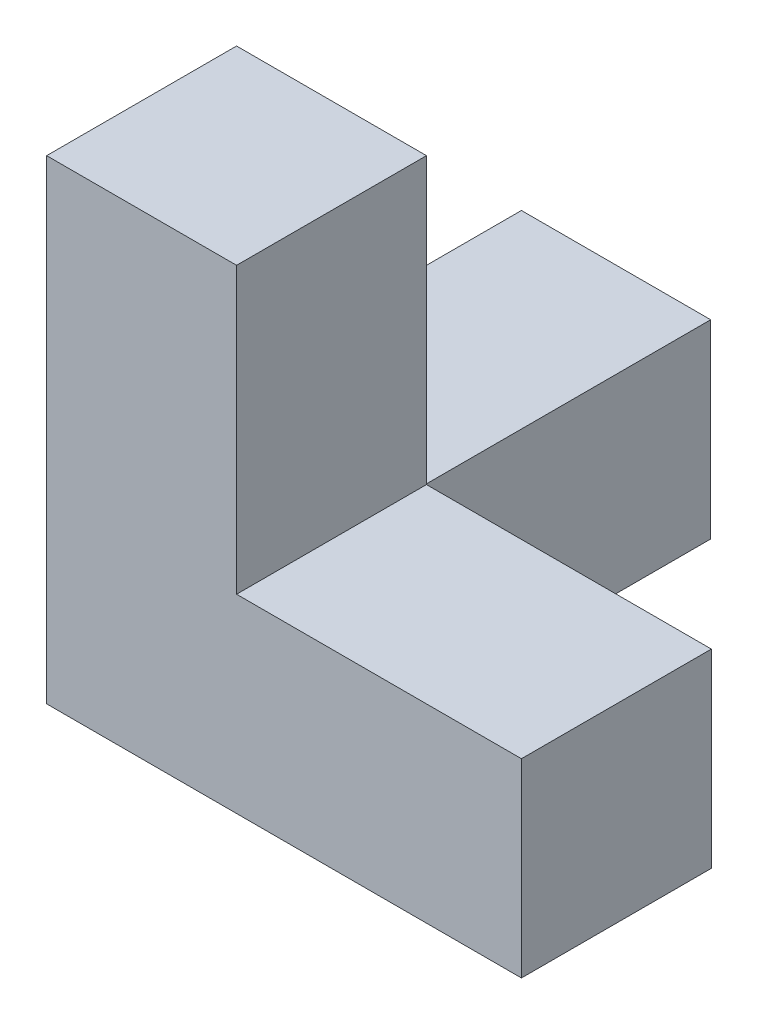
SolidWorks part; units mm, degrees
ref_plane "Plan de face" through (0, 0, 0) normal (0, 0, 1) x (1, 0, 0)
ref_plane "Plan de dessus" through (0, 0, 0) normal (0, 1, 0) x (1, 0, 0)
ref_plane "Plan de droite" through (0, 0, 0) normal (1, 0, 0) x (0, 0, -1)
sketch "Esquisse2" plane through (0, 0, 0) normal (0, 0, 1) x (1, 0, 0)
  line L1 (-109.7222, 44.9846) -> (-59.7222, 44.9846)
  line L2 (-109.7222, 44.9846) -> (-109.7222, -5.0154)
  line L3 (-109.7222, -5.0154) -> (-59.7222, -5.0154)
  line L4 (-59.7222, 44.9846) -> (-59.7222, -5.0154)
  line L5 (-109.7222, 44.9846) -> (-59.7222, -5.0154) construction
  line L6 (-109.7222, -5.0154) -> (-59.7222, 44.9846) construction
  point P0 (-84.7222, 19.9846)
  dimension "D1" = 50
  dimension "D2" = 50
  dimension "D3" = 50
  dimension "D4" = 50
extrude "Boss.-Extru.1" add sketch "Esquisse2" along normal blind 50
sketch "Esquisse3" plane through (0, 0, 50) normal (0, 0, 1) x (1, 0, 0)
  line L0 (-89.7222, 44.9846) -> (-89.7222, 14.9846)
  line L1 (-59.7222, 44.9846) -> (-109.7222, 44.9846) construction
  line L2 (-89.7222, 14.9846) -> (-59.7222, 14.9846)
  line L3 (-59.7222, -5.0154) -> (-59.7222, 44.9846) construction
  dimension "D1" = 20
  dimension "D2" = 20
extrude "Enlèv. mat.-Extru.1" cut sketch "Esquisse3" against normal blind 50 and the other way through all
sketch "Esquisse4" plane through (0, 0, 0) normal (0, 0, -1) x (-1, 0, 0)
  line L0 (89.7222, 14.9846) -> (109.7222, 14.9846)
  line L1 (109.7222, 44.9846) -> (109.7222, -5.0154) construction
extrude "Enlèv. mat.-Extru.2" cut sketch "Esquisse4" against normal blind 30 and the other way through all
sketch "Esquisse5" plane through (0, 0, 0) normal (0, 0, -1) x (-1, 0, 0)
  line L0 (89.7925, 14.9846) -> (89.7925, -5.0154)
  line L1 (109.7222, 14.9846) -> (59.7222, 14.9846) construction
  line L2 (109.7222, -5.0154) -> (59.7222, -5.0154) construction
extrude "Enlèv. mat.-Extru.3" cut sketch "Esquisse5" against normal blind 30 and the other way through all flip side to cut
